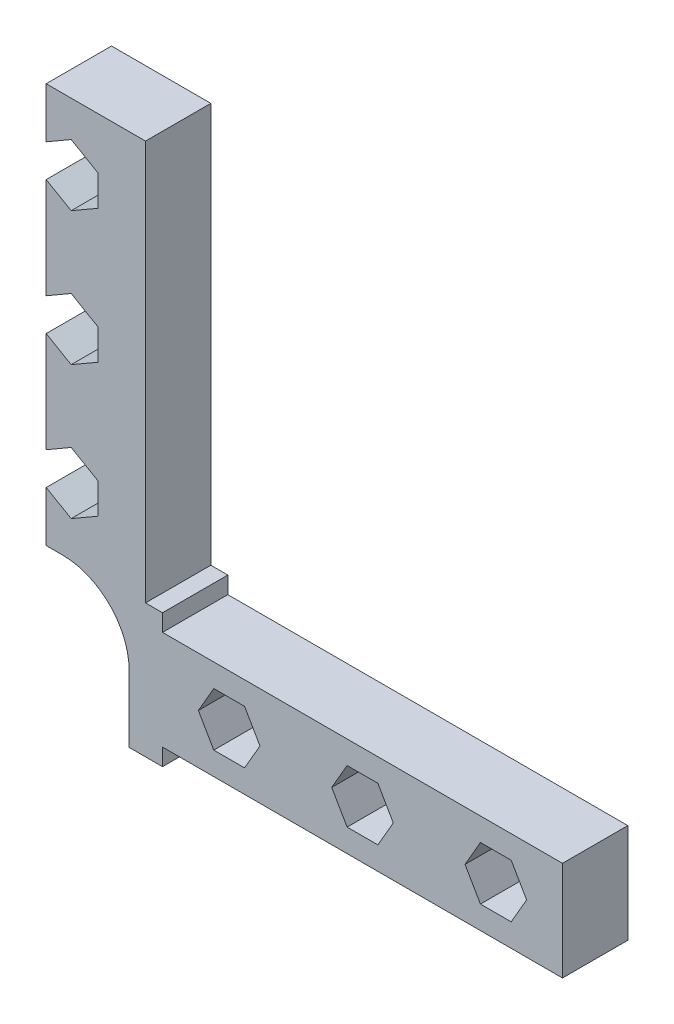
SolidWorks part; units mm, degrees
material "ABS"
ref_plane "Front" through (0, 0, 0) normal (0, 0, 1) x (1, 0, 0)
ref_plane "Top" through (0, 0, 0) normal (0, 1, 0) x (1, 0, 0)
ref_plane "Right" through (0, 0, 0) normal (1, 0, 0) x (0, 0, -1)
sketch "Sketch1" plane through (0, 0, 0) normal (0, 0, 1) x (1, 0, 0)
  line L0 (0, 0) -> (0, 25.4)
  line L1 (0, 25.4) -> (3.2385, 25.4)
  line L2 (3.2385, 25.4) -> (3.2385, 101.6)
  line L3 (3.2385, 101.6) -> (22.1615, 101.6)
  line L4 (22.1615, 101.6) -> (22.1615, 25.4)
  line L5 (22.1615, 25.4) -> (25.4, 25.4)
  line L6 (25.4, 25.4) -> (25.4, 22.1615)
  line L7 (25.4, 22.1615) -> (101.6, 22.1615)
  line L8 (101.6, 22.1615) -> (101.6, 3.2385)
  line L9 (101.6, 3.2385) -> (25.4, 3.2385)
  line L10 (25.4, 3.2385) -> (25.4, 0)
  line L11 (25.4, 0) -> (0, 0)
  dimension "D1" = 25.4
  dimension "D2" = 76.2
  dimension "D3" = 18.923
extrude "Boss-Extrude1" add sketch "Sketch1" along normal blind 12.446
sketch "Sketch2" plane through (0, 0, 12.446) normal (0, 0, 1) x (1, 0, 0)
  line L2 (0, 25.4) -> (0, 0) construction
  line L3 (3.2385, 25.4) -> (0, 25.4) construction
  line L4 (6.35, 25.4) -> (0, 25.4)
  line L5 (0, 25.4) -> (0, 0)
  line L7 (0, 0) -> (19.05, 0)
  line L8 (0, 0) -> (25.4, 0) construction
  line L9 (19.05, 0) -> (19.05, 12.7)
  arc A1 (6.35, 25.4) -> (19.05, 12.7) centre (6.35, 12.7) cw
  dimension "D1" = 6.35
  dimension "D2" = 12.7
extrude "Cut-Extrude1" cut sketch "Sketch2" against normal through all
hole_wizard "#10 Clearance Hole1" positions "Sketch3" profile "Sketch4" hole size "#10" standard "ANSI Inch" end condition through all
sketch "Sketch3" plane through (0, 0, 12.446) normal (0, 0, 1) x (1, 0, 0)
  line L0 (8.001, 101.6) -> (8.001, 12.7) construction
  line L1 (22.1615, 101.6) -> (3.2385, 101.6) construction
  line L2 (8.001, 12.7) -> (101.6, 12.7) construction
  line L3 (101.6, 3.2385) -> (101.6, 22.1615) construction
  line L4 (3.2385, 101.6) -> (3.2385, 25.4) construction
  point P11 (8.001, 88.9)
  point P13 (8.001, 63.5)
  point P15 (8.001, 38.1)
  point P17 (38.1, 12.7)
  point P19 (63.5, 12.7)
  point P21 (88.9, 12.7)
  dimension "D1" = 12.7
  dimension "D2" = 25.4
  dimension "D3" = 25.4
  dimension "D4" = 25.4
  dimension "D5" = 25.4
  dimension "D6" = 12.7
  dimension "D7" = 4.7625
sketch "Sketch4" plane through (88.9, 12.7, 12.446) normal (1, 0, 0) x (0, -1, 0)
  line L0 (0, 0) -> (0, 12.446)
  line L1 (0, 12.446) -> (2.5527, 12.446)
  line L2 (2.5527, 12.446) -> (2.5527, 0)
  line L5 (2.5527, 0) -> (0, 0)
  line L11 (0, -6.35) -> (0, 107.95) construction
  dimension "Thru Hole Dia." = 5.1054
  dimension "Thru Hole Depth" = 12.446
sketch "Sketch5" plane through (0, 0, 12.446) normal (0, 0, 1) x (1, 0, 0)
  line L1 (13.081, 85.9671) -> (13.081, 91.8329)
  line L2 (13.081, 91.8329) -> (8.001, 94.7659)
  line L3 (8.001, 94.7659) -> (2.921, 91.8329)
  line L4 (2.921, 91.8329) -> (2.921, 85.9671)
  line L5 (2.921, 85.9671) -> (8.001, 83.0341)
  line L6 (8.001, 83.0341) -> (13.081, 85.9671)
  line L7 (13.081, 60.5671) -> (13.081, 66.4329)
  line L8 (13.081, 66.4329) -> (8.001, 69.3659)
  line L9 (8.001, 69.3659) -> (2.921, 66.4329)
  line L10 (2.921, 66.4329) -> (2.921, 60.5671)
  line L11 (2.921, 60.5671) -> (8.001, 57.6341)
  line L12 (8.001, 57.6341) -> (13.081, 60.5671)
  line L13 (13.081, 35.1671) -> (13.081, 41.0329)
  line L14 (13.081, 41.0329) -> (8.001, 43.9659)
  line L15 (8.001, 43.9659) -> (2.921, 41.0329)
  line L16 (2.921, 41.0329) -> (2.921, 35.1671)
  line L17 (2.921, 35.1671) -> (8.001, 32.2341)
  line L18 (8.001, 32.2341) -> (13.081, 35.1671)
  line L19 (41.0329, 7.62) -> (43.9659, 12.7)
  line L20 (43.9659, 12.7) -> (41.0329, 17.78)
  line L21 (41.0329, 17.78) -> (35.1671, 17.78)
  line L22 (35.1671, 17.78) -> (32.2341, 12.7)
  line L23 (32.2341, 12.7) -> (35.1671, 7.62)
  line L24 (35.1671, 7.62) -> (41.0329, 7.62)
  line L25 (66.4329, 7.62) -> (69.3659, 12.7)
  line L26 (69.3659, 12.7) -> (66.4329, 17.78)
  line L27 (66.4329, 17.78) -> (60.5671, 17.78)
  line L28 (60.5671, 17.78) -> (57.6341, 12.7)
  line L29 (57.6341, 12.7) -> (60.5671, 7.62)
  line L30 (60.5671, 7.62) -> (66.4329, 7.62)
  line L31 (91.8329, 7.62) -> (94.7659, 12.7)
  line L32 (94.7659, 12.7) -> (91.8329, 17.78)
  line L33 (91.8329, 17.78) -> (85.9671, 17.78)
  line L34 (85.9671, 17.78) -> (83.0341, 12.7)
  line L35 (83.0341, 12.7) -> (85.9671, 7.62)
  line L36 (85.9671, 7.62) -> (91.8329, 7.62)
  circle A0 centre (8.001, 88.9) radius 5.08 construction
  circle A1 centre (8.001, 63.5) radius 5.08 construction
  circle A2 centre (8.001, 38.1) radius 5.08 construction
  circle A3 centre (38.1, 12.7) radius 5.08 construction
  circle A4 centre (63.5, 12.7) radius 5.08 construction
  circle A5 centre (88.9, 12.7) radius 5.08 construction
  dimension "D1" = 10.16
  dimension "D2" = 10.16
extrude "Cut-Extrude2" cut sketch "Sketch5" against normal through all
